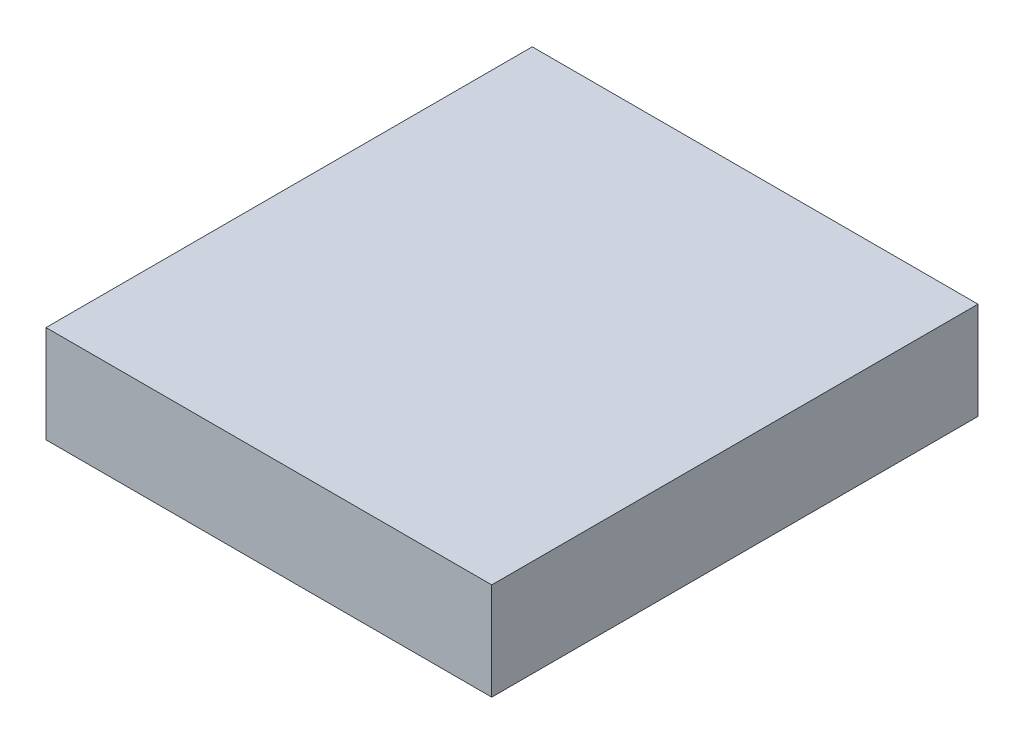
SolidWorks part; units mm, degrees
ref_plane "Front Plane" through (0, 0, 0) normal (0, 0, 1) x (1, 0, 0)
ref_plane "Top Plane" through (0, 0, 0) normal (0, 1, 0) x (1, 0, 0)
ref_plane "Right Plane" through (0, 0, 0) normal (1, 0, 0) x (0, 0, -1)
sketch "Sketch1" plane through (0, 0, 0) normal (0, 1, 0) x (1, 0, 0)
  line L1 (55, -60) -> (-55, -60)
  line L2 (55, -60) -> (55, 60)
  line L3 (55, 60) -> (-55, 60)
  line L4 (-55, -60) -> (-55, 60)
  line L5 (55, -60) -> (-55, 60) construction
  line L6 (55, 60) -> (-55, -60) construction
  point P0 (0, 0)
  dimension "D1" = 110
  dimension "D2" = 120
extrude "Boss-Extrude1" add sketch "Sketch1" along normal blind 24
sketch "Sketch2" plane through (0, 24, 0) normal (0, 1, 0) x (1, 0, 0)
  text T0 "Li Pol 2S2P"
